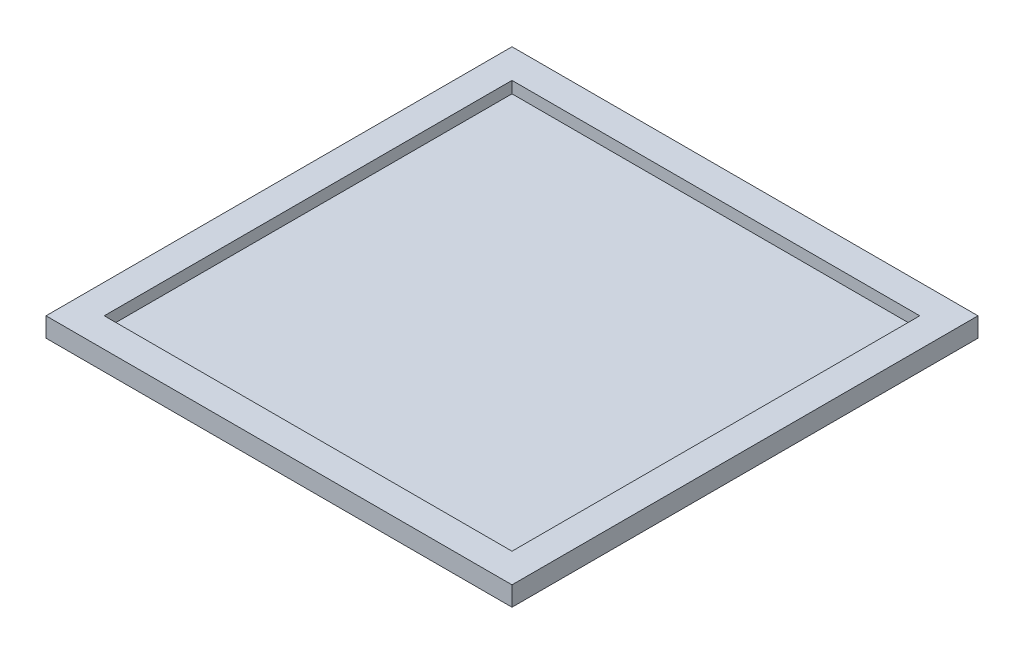
SolidWorks part; units mm, degrees
ref_plane "Спереди" through (0, 0, 0) normal (0, 0, 1) x (1, 0, 0)
ref_plane "Сверху" through (0, 0, 0) normal (0, 1, 0) x (1, 0, 0)
ref_plane "Справа" through (0, 0, 0) normal (1, 0, 0) x (0, 0, -1)
sketch "Эскиз1" plane through (0, 0, 0) normal (0, 1, 0) x (1, 0, 0)
  line L1 (-60, -60) -> (60, -60)
  line L2 (-60, -60) -> (-60, 60)
  line L3 (-60, 60) -> (60, 60)
  line L4 (60, -60) -> (60, 60)
  line L5 (-60, -60) -> (60, 60) construction
  line L6 (-60, 60) -> (60, -60) construction
  point P0 (0, 0)
extrude "Бобышка-Вытянуть1" add sketch "Эскиз1" along normal blind 5
sketch "Эскиз2" plane through (0, 5, 0) normal (0, 1, 0) x (1, 0, 0)
  line L1 (-52.5, -52.5) -> (52.5, -52.5)
  line L2 (-52.5, -52.5) -> (-52.5, 52.5)
  line L3 (-52.5, 52.5) -> (52.5, 52.5)
  line L4 (52.5, -52.5) -> (52.5, 52.5)
  line L5 (-52.5, -52.5) -> (52.5, 52.5) construction
  line L6 (-52.5, 52.5) -> (52.5, -52.5) construction
  point P0 (0, 0)
extrude "Вырез-Вытянуть1" cut sketch "Эскиз2" against normal blind 3
